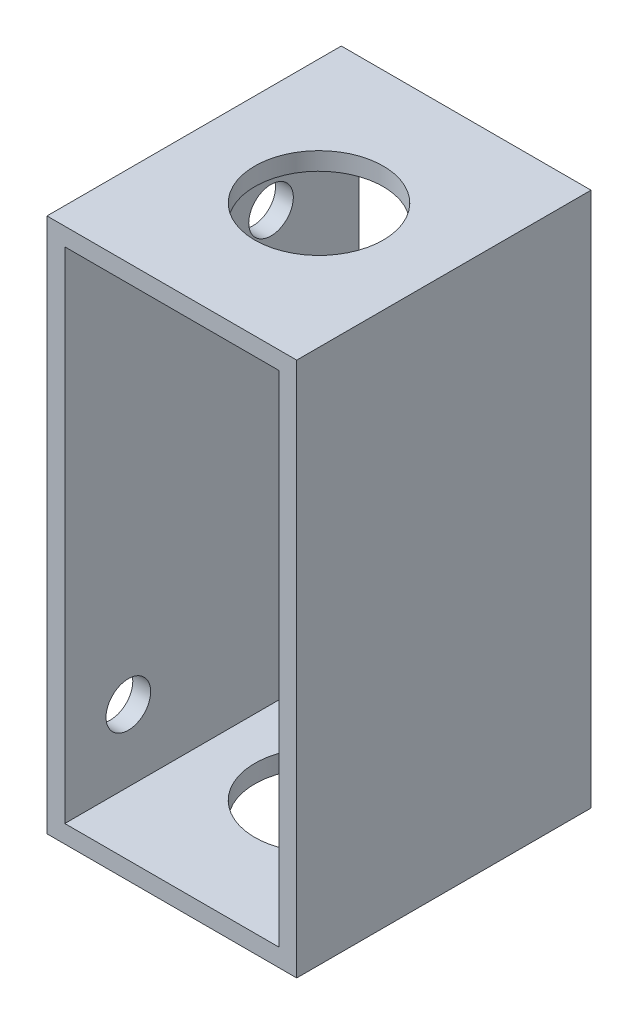
SolidWorks part; units mm, degrees
ref_plane "Front Plane" through (0, 0, 0) normal (0, 0, 1) x (1, 0, 0)
ref_plane "Top Plane" through (0, 0, 0) normal (0, 1, 0) x (1, 0, 0)
ref_plane "Right Plane" through (0, 0, 0) normal (1, 0, 0) x (0, 0, -1)
sketch "Sketch1" plane through (0, 0, 0) normal (0, 0, 1) x (1, 0, 0)
  line L1 (0, 0) -> (14, 0)
  line L2 (0, 0) -> (0, 30)
  line L3 (0, 30) -> (14, 30)
  line L4 (14, 0) -> (14, 30)
  dimension "D1" = 30
  dimension "D2" = 14
extrude "Boss-Extrude1" add sketch "Sketch1" along normal blind 16.5
sketch "Sketch3" plane through (0, 0, 0) normal (0, 0, 1) x (1, 0, 0)
  line L1 (0, 30) -> (14, 30)
  line L2 (0, 30) -> (0, 0)
  line L3 (0, 0) -> (14, 0)
  line L4 (14, 30) -> (14, 0)
  line L8 (1, 29) -> (13, 29)
  line L9 (13, 29) -> (13, 1)
  line L10 (1, 1) -> (13, 1)
  line L11 (1, 29) -> (1, 1)
  point P10 (15, 31)
  point P11 (0, 0)
  point P12 (0, 0)
  dimension "D1" = 1
extrude "Cut-Extrude3" cut sketch "Sketch3" against normal through all and the other way through all flip side to cut
sketch "Sketch4" plane through (0, 0, 0) normal (0, 1, 0) x (1, 0, 0)
  line L0 (0, -16.5) -> (14, 0) construction
  circle A0 centre (7, -8.25) radius 3.6
  point P6 (7, -8.25)
  point P7 (0, 0)
  dimension "D1" = 7.2
extrude "Cut-Extrude4" cut sketch "Sketch4" along direction (0, -1, 0) on the side against the normal blind 16.5 and the other way through all
sketch "Sketch5" plane through (0, 0, 0) normal (1, 0, 0) x (0, 0, -1)
  line L0 (-16.5, 30) -> (0, 30) construction
  circle A0 centre (-4.9397, 25) radius 1.25
  circle A1 centre (-12.9397, 5) radius 1.25
  dimension "D4" = 2.5
  dimension "D5" = 2.5
  dimension "D1" = 5
  dimension "D2" = 8
  dimension "D3" = 20
extrude "Cut-Extrude6" cut sketch "Sketch5" along direction (-1, 0, 0) on the side of the normal up to surface (1 mm away)
